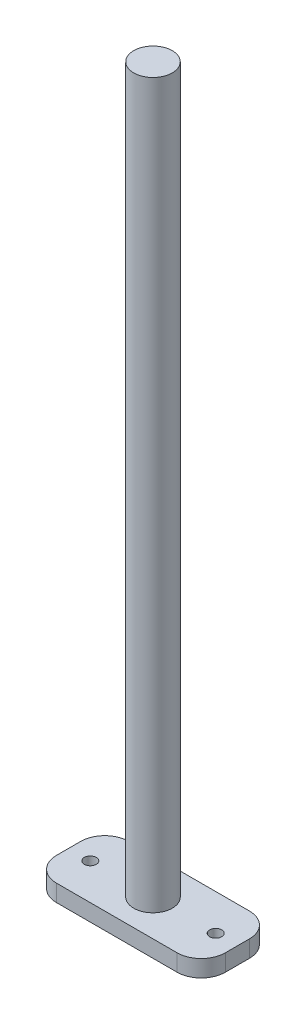
SolidWorks part; units mm, degrees
ref_plane "Alzado" through (0, 0, 0) normal (0, 0, 1) x (1, 0, 0)
ref_plane "Planta" through (0, 0, 0) normal (0, 1, 0) x (1, 0, 0)
ref_plane "Vista lateral" through (0, 0, 0) normal (1, 0, 0) x (0, 0, -1)
sketch "Croquis1" plane through (0, 0, 0) normal (0, 1, 0) x (1, 0, 0)
  line L0 (-40.0578, 0) -> (39.1865, 0) construction
  line L1 (-12.5, 7.5) -> (12.5, 7.5)
  line L2 (-17.5, 2.5) -> (-17.5, -2.5)
  line L3 (-12.5, -7.5) -> (12.5, -7.5)
  line L4 (17.5, 2.5) -> (17.5, -2.5)
  line L5 (-17.5, 7.5) -> (17.5, -7.5) construction
  line L6 (-17.5, -7.5) -> (17.5, 7.5) construction
  circle A0 centre (-13, 0) radius 1.25
  circle A1 centre (13, 0) radius 1.25
  arc A2 (-17.5, 2.5) -> (-12.5, 7.5) centre (-12.5, 2.5) cw
  arc A3 (-12.5, -7.5) -> (-17.5, -2.5) centre (-12.5, -2.5) cw
  arc A4 (17.5, -2.5) -> (12.5, -7.5) centre (12.5, -2.5) cw
  arc A5 (17.5, 2.5) -> (12.5, 7.5) centre (12.5, 2.5) ccw
  circle A6 centre (0, 0) radius 4
  point P0 (0, 0)
  dimension "D3" = 2.5
  dimension "D4" = 2.5
  dimension "D7" = 5
  dimension "D8" = 5
  dimension "D9" = 5
  dimension "D10" = 5
  dimension "D11" = 8
  dimension "D1" = 15
  dimension "D2" = 35
  dimension "D5" = 4.5
  dimension "D6" = 4.5
extrude "Saliente-Extruir1" add sketch "Croquis1" along normal blind 3.5 contours A6 | L4 A5 L1 A2 L2 A3 L3 A4 A6 A0 A1
sketch "Croquis2" plane through (0, 3.5, 0) normal (0, 1, 0) x (1, 0, 0)
  circle A0 centre (0, 0) radius 4
  dimension "D1" = 8
extrude "Saliente-Extruir2" add sketch "Croquis2" along normal blind 150 contours A0
